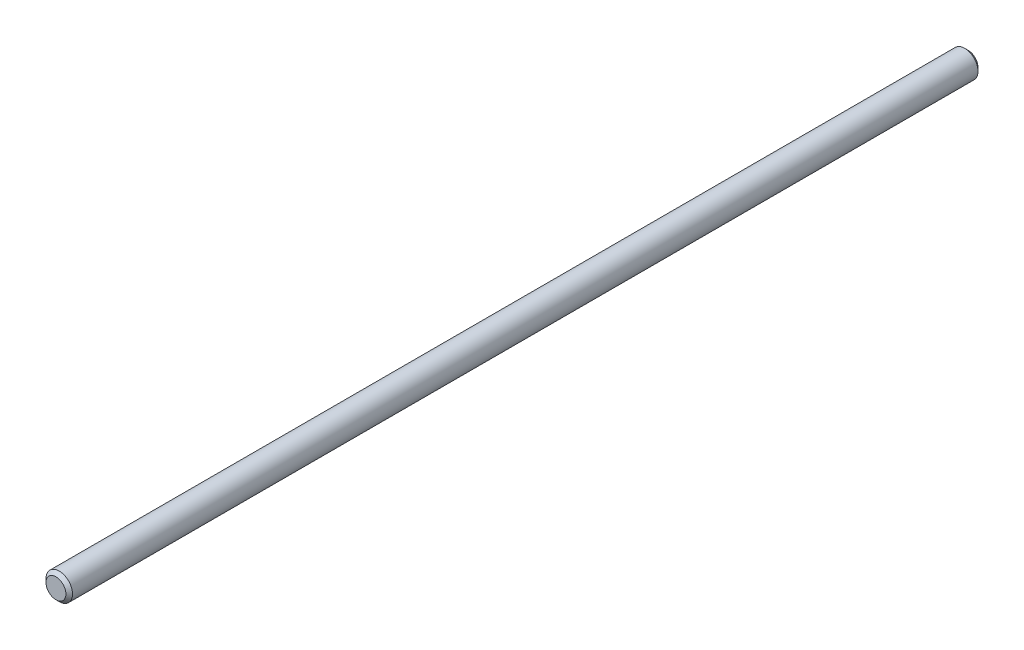
SolidWorks part; units mm, degrees
material "Plain Carbon Steel"
ref_plane "Спереди" through (0, 0, 0) normal (0, 0, 1) x (1, 0, 0)
ref_plane "Сверху" through (0, 0, 0) normal (0, 1, 0) x (1, 0, 0)
ref_plane "Справа" through (0, 0, 0) normal (1, 0, 0) x (0, 0, -1)
sketch "Sketch1" plane through (0, 0, 0) normal (0, 0, 1) x (1, 0, 0)
  circle A0 centre (0, 0) radius 4
  dimension "D1" = 8
extrude "Boss-Extrude1" add sketch "Sketch1" along normal blind 275
chamfer "Chamfer1" distance 1 angle 45 2 edges at (4, 0, 275) (4, 0, 0)
